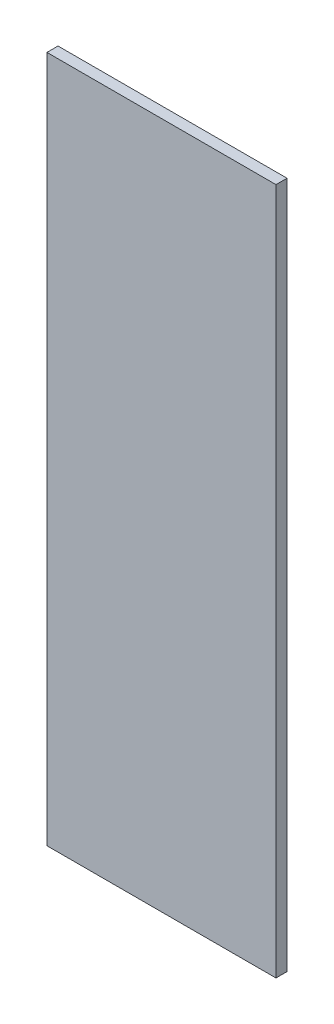
SolidWorks part; units mm, degrees
ref_plane "Alzado" through (0, 0, 0) normal (0, 0, 1) x (1, 0, 0)
ref_plane "Planta" through (0, 0, 0) normal (0, 1, 0) x (1, 0, 0)
ref_plane "Vista lateral" through (0, 0, 0) normal (1, 0, 0) x (0, 0, -1)
sketch "Croquis1" plane through (0, 0, 0) normal (0, 0, 1) x (1, 0, 0)
  line L1 (0, 0) -> (60, 0)
  line L2 (0, 0) -> (0, 180)
  line L3 (0, 180) -> (60, 180)
  line L4 (60, 0) -> (60, 180)
  dimension "D1" = 180
  dimension "D2" = 60
extrude "Saliente-Extruir1" add sketch "Croquis1" along normal blind 2.9
